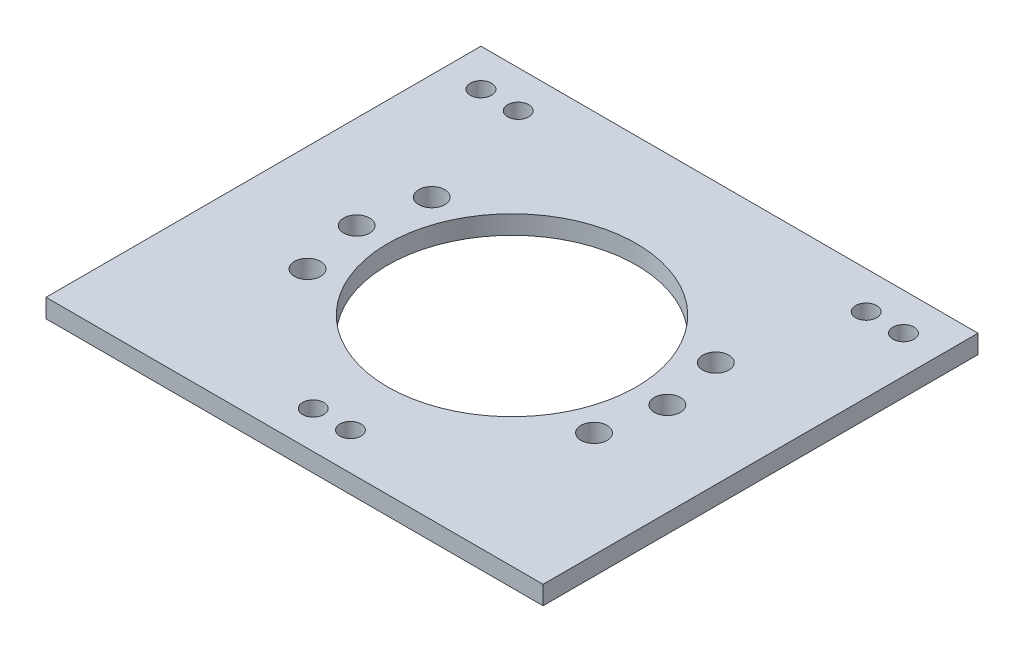
SolidWorks part; units mm, degrees
ref_plane "Front Plane" through (0, 0, 0) normal (0, 0, 1) x (1, 0, 0)
ref_plane "Top Plane" through (0, 0, 0) normal (0, 1, 0) x (1, 0, 0)
ref_plane "Right Plane" through (0, 0, 0) normal (1, 0, 0) x (0, 0, -1)
sketch "Base" plane through (0, 0, 0) normal (0, 1, 0) x (1, 0, 0)
  line L1 (40, -35) -> (-40, -35)
  line L2 (40, -35) -> (40, 35)
  line L3 (40, 35) -> (-40, 35)
  line L4 (-40, -35) -> (-40, 35)
  line L5 (40, -35) -> (-40, 35) construction
  line L6 (40, 35) -> (-40, -35) construction
  point P0 (0, 0)
  dimension "D1" = 70
  dimension "D2" = 80
extrude "Base Plate" add sketch "Base" along normal blind 3
sketch "Extruder hole" plane through (0, 3, 0) normal (0, 1, 0) x (1, 0, 0)
  circle A0 centre (0, 0) radius 20
  dimension "D1" = 40
extrude "Extruder Hole Cut" cut sketch "Extruder hole" against normal up to next
sketch "Extruder Mount Holes" plane through (0, 3, 0) normal (0, 1, 0) x (1, 0, 0)
  line L0 (-40, 0) -> (40, 0) construction
  line L1 (-40, 35) -> (-40, -35) construction
  line L2 (40, -35) -> (40, 35) construction
  circle A0 centre (-25, 0) radius 2.1
  circle A1 centre (-22.9129, 10) radius 2.1
  circle A2 centre (-22.9129, -10) radius 2.1
  circle A3 centre (25, 0) radius 2.1
  circle A4 centre (23, 9.798) radius 2.1
  circle A5 centre (23, -9.798) radius 2.1
  dimension "D1" = 4.2
  dimension "D2" = 25
  dimension "D3" = 25
  dimension "D7" = 25
  dimension "D4" = 25
  dimension "D5" = 10
  dimension "D6" = 10
  dimension "D8" = 25
  dimension "D9" = 25
  dimension "D10" = 10
  dimension "D11" = 10
extrude "Extruder Srew Holes Cut" cut sketch "Extruder Mount Holes" against normal up to next
sketch "LM8uu Holes" plane through (0, 3, 0) normal (0, 1, 0) x (1, 0, 0)
  line L0 (40, 35) -> (-40, 35) construction
  line L1 (-40, 35) -> (-40, -35) construction
  line L2 (40, -35) -> (40, 35) construction
  circle A0 centre (-34, 29) radius 1.7
  circle A1 centre (-28, 29) radius 1.7
  circle A2 centre (28, 29) radius 1.7
  circle A3 centre (34, 29) radius 1.7
  dimension "D1" = 3.4
  dimension "D5" = 6
  dimension "D2" = 6
  dimension "D3" = 6
  dimension "D4" = 6
  dimension "D6" = 6
sketch "LM8uu Center" plane through (0, 3, 0) normal (0, 1, 0) x (1, 0, 0)
  line L0 (0, -35) -> (0, 107.229) construction
  line L1 (-40, -35) -> (40, -35) construction
  circle A0 centre (-3, -29) radius 1.7
  circle A1 centre (3, -29) radius 1.7
  dimension "D1" = 3.4
  dimension "D2" = 3
  dimension "D3" = 6
  dimension "D4" = 6
extrude "LM8 Two" cut sketch "LM8uu Holes" against normal up to next
extrude "LM8 Center" cut sketch "LM8uu Center" against normal up to next
